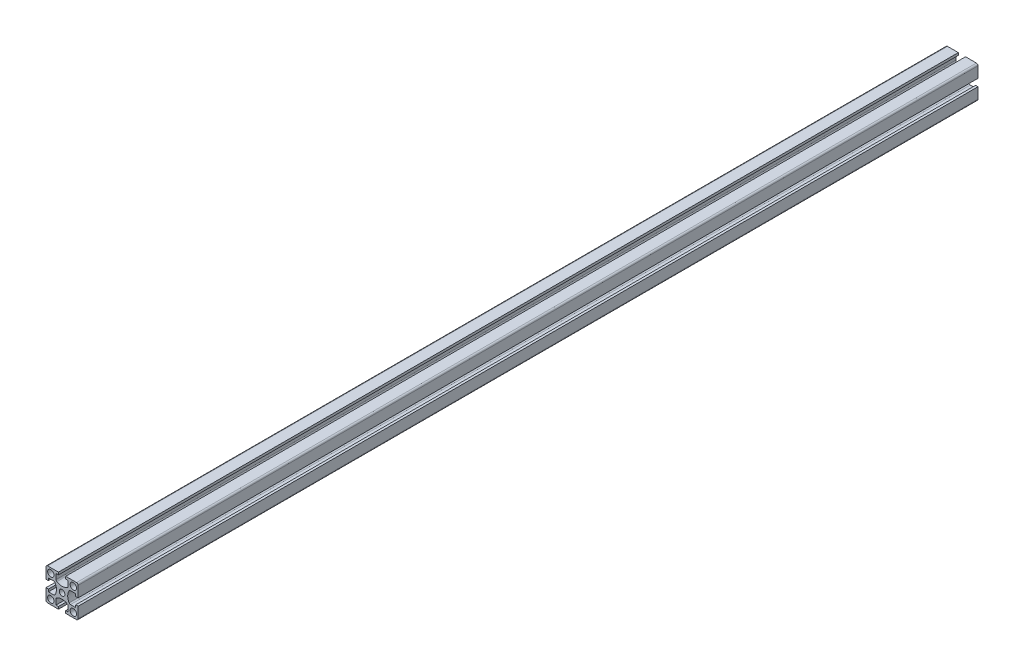
SolidWorks part; units mm, degrees
ref_plane "Front Plane" through (0, 0, 0) normal (0, 0, 1) x (1, 0, 0)
ref_plane "Top Plane" through (0, 0, 0) normal (0, 1, 0) x (1, 0, 0)
ref_plane "Right Plane" through (0, 0, 0) normal (1, 0, 0) x (0, 0, -1)
sketch "Sketch1" plane through (0, 0, 0) normal (0, 0, 1) x (1, 0, 0)
  line L64 (-12.5, 11.25) -> (-12.5, 2.8125)
  line L65 (-12.5, 2.8125) -> (-10.625, 2.8125)
  line L66 (-10.625, 2.8125) -> (-10.625, 4.6875)
  line L67 (-10.625, 4.6875) -> (-6.5461, 4.6875)
  line L68 (-6.5461, -4.6875) -> (-10.625, -4.6875)
  line L69 (-10.625, -4.6875) -> (-10.625, -2.8125)
  line L70 (-10.625, -2.8125) -> (-12.5, -2.8125)
  line L71 (-12.5, -2.8125) -> (-12.5, -11.25)
  line L72 (-11.25, -12.5) -> (-2.8125, -12.5)
  line L73 (-2.8125, -12.5) -> (-2.8125, -10.625)
  line L74 (-2.8125, -10.625) -> (-4.6875, -10.625)
  line L75 (-4.6875, -10.625) -> (-4.6875, -6.5461)
  line L76 (4.6875, -6.5461) -> (4.6875, -10.625)
  line L77 (4.6875, -10.625) -> (2.8125, -10.625)
  line L78 (2.8125, -10.625) -> (2.8125, -12.5)
  line L79 (2.8125, -12.5) -> (11.25, -12.5)
  line L80 (12.5, -11.25) -> (12.5, -2.8125)
  line L81 (12.5, -2.8125) -> (10.625, -2.8125)
  line L82 (10.625, -2.8125) -> (10.625, -4.6875)
  line L83 (10.625, -4.6875) -> (6.5461, -4.6875)
  line L84 (6.5461, 4.6875) -> (10.625, 4.6875)
  line L85 (10.625, 4.6875) -> (10.625, 2.8125)
  line L86 (10.625, 2.8125) -> (12.5, 2.8125)
  line L87 (12.5, 2.8125) -> (12.5, 11.25)
  line L88 (11.25, 12.5) -> (2.8125, 12.5)
  line L89 (2.8125, 12.5) -> (2.8125, 10.625)
  line L90 (2.8125, 10.625) -> (4.6875, 10.625)
  line L91 (4.6875, 10.625) -> (4.6875, 6.5461)
  line L92 (-4.6875, 6.5461) -> (-4.6875, 10.625)
  line L93 (-4.6875, 10.625) -> (-2.8125, 10.625)
  line L94 (-2.8125, 10.625) -> (-2.8125, 12.5)
  line L95 (-2.8125, 12.5) -> (-11.25, 12.5)
  circle A5 centre (-8.75, -8.75) radius 2.5
  circle A6 centre (8.75, -8.75) radius 2.5
  circle A7 centre (8.75, 8.75) radius 2.5
  circle A8 centre (0, 0) radius 2.1875
  circle A9 centre (-8.75, 8.75) radius 2.5
  arc A32 (-11.25, 12.5) -> (-12.5, 11.25) centre (-11.25, 11.25) ccw
  arc A33 (-5.4635, 4.0625) -> (-6.5461, 4.6875) centre (-6.5461, 3.4375) ccw
  arc A34 (-5.4635, -4.0625) -> (-5.4635, 4.0625) centre (-12.5, 0) ccw
  arc A35 (-6.5461, -4.6875) -> (-5.4635, -4.0625) centre (-6.5461, -3.4375) ccw
  arc A36 (-12.5, -11.25) -> (-11.25, -12.5) centre (-11.25, -11.25) ccw
  arc A37 (-4.0625, -5.4635) -> (-4.6875, -6.5461) centre (-3.4375, -6.5461) ccw
  arc A38 (4.0625, -5.4635) -> (-4.0625, -5.4635) centre (0, -12.5) ccw
  arc A39 (4.6875, -6.5461) -> (4.0625, -5.4635) centre (3.4375, -6.5461) ccw
  arc A40 (11.25, -12.5) -> (12.5, -11.25) centre (11.25, -11.25) ccw
  arc A41 (5.4635, -4.0625) -> (6.5461, -4.6875) centre (6.5461, -3.4375) ccw
  arc A42 (5.4635, 4.0625) -> (5.4635, -4.0625) centre (12.5, 0) ccw
  arc A43 (6.5461, 4.6875) -> (5.4635, 4.0625) centre (6.5461, 3.4375) ccw
  arc A44 (12.5, 11.25) -> (11.25, 12.5) centre (11.25, 11.25) ccw
  arc A45 (4.0625, 5.4635) -> (4.6875, 6.5461) centre (3.4375, 6.5461) ccw
  arc A46 (-4.0625, 5.4635) -> (4.0625, 5.4635) centre (0, 12.5) ccw
  arc A47 (-4.6875, 6.5461) -> (-4.0625, 5.4635) centre (-3.4375, 6.5461) ccw
extrude "Boss-Extrude1" add sketch "Sketch1" along normal blind 700
